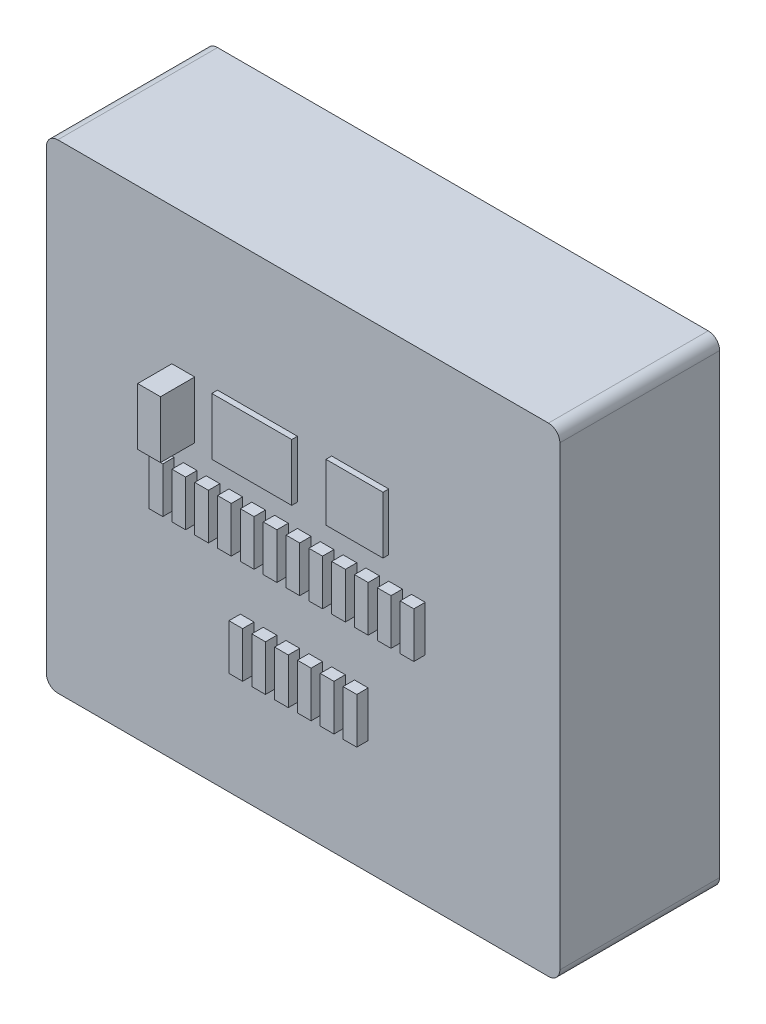
SolidWorks part; units mm, degrees
ref_plane "Front Plane" through (0, 0, 0) normal (0, 0, 1) x (1, 0, 0)
ref_plane "Top Plane" through (0, 0, 0) normal (0, 1, 0) x (1, 0, 0)
ref_plane "Right Plane" through (0, 0, 0) normal (1, 0, 0) x (0, 0, -1)
sketch "Sketch1" plane through (0, 0, 0) normal (0, 0, 1) x (1, 0, 0)
  line L1 (1, 0) -> (44, 0)
  line L2 (0, 1) -> (0, 41)
  line L3 (1, 42) -> (44, 42)
  line L4 (45, 1) -> (45, 41)
  arc A0 (1, 0) -> (0, 1) centre (1, 1) cw
  arc A1 (44, 0) -> (45, 1) centre (44, 1) ccw
  arc A2 (44, 42) -> (45, 41) centre (44, 41) cw
  arc A3 (0, 41) -> (1, 42) centre (1, 41) cw
  point P7 (0, 0)
  point P12 (45, 42)
  point P15 (0, 42)
  dimension "D3" = 1
  dimension "D1" = 42
  dimension "D2" = 45
extrude "Boss-Extrude1" add sketch "Sketch1" along normal blind 14
sketch "Sketch2" plane through (0, 0, 14) normal (0, 0, 1) x (1, 0, 0)
  line L0 (44, 42) -> (1, 42) construction
  line L1 (15, 30) -> (22, 30)
  line L2 (15, 30) -> (15, 25)
  line L3 (15, 25) -> (22, 25)
  line L4 (22, 30) -> (22, 25)
  line L5 (25, 30) -> (30, 30)
  line L6 (25, 30) -> (25, 25)
  line L7 (25, 25) -> (30, 25)
  line L8 (30, 30) -> (30, 25)
  line L9 (0, 41) -> (0, 1) construction
  line L10 (45, 1) -> (45, 41) construction
  dimension "D1" = 7
  dimension "D2" = 5
  dimension "D3" = 5
  dimension "D4" = 5
  dimension "D5" = 12
  dimension "D6" = 15
  dimension "D7" = 15
extrude "Boss-Extrude2" add sketch "Sketch2" along normal blind 0.5
sketch "Sketch3" plane through (0, 0, 14) normal (0, 0, 1) x (1, 0, 0)
  line L0 (0, 41) -> (0, 1) construction
  line L1 (10, 23) -> (11.2, 23)
  line L2 (10, 23) -> (10, 19)
  line L3 (10, 19) -> (11.2, 19)
  line L4 (11.2, 23) -> (11.2, 19)
  line L5 (1, 0) -> (44, 0) construction
  line L6 (12, 23) -> (13.2, 23)
  line L7 (13.2, 23) -> (13.2, 19)
  line L8 (12, 19) -> (13.2, 19)
  line L9 (12, 23) -> (12, 19)
  line L10 (14, 23) -> (15.2, 23)
  line L11 (15.2, 23) -> (15.2, 19)
  line L12 (14, 19) -> (15.2, 19)
  line L13 (14, 23) -> (14, 19)
  line L14 (16, 23) -> (17.2, 23)
  line L15 (17.2, 23) -> (17.2, 19)
  line L16 (16, 19) -> (17.2, 19)
  line L17 (16, 23) -> (16, 19)
  line L18 (18, 23) -> (19.2, 23)
  line L19 (19.2, 23) -> (19.2, 19)
  line L20 (18, 19) -> (19.2, 19)
  line L21 (18, 23) -> (18, 19)
  line L22 (20, 23) -> (21.2, 23)
  line L23 (21.2, 23) -> (21.2, 19)
  line L24 (20, 19) -> (21.2, 19)
  line L25 (20, 23) -> (20, 19)
  line L26 (22, 23) -> (23.2, 23)
  line L27 (23.2, 23) -> (23.2, 19)
  line L28 (22, 19) -> (23.2, 19)
  line L29 (22, 23) -> (22, 19)
  line L30 (24, 23) -> (25.2, 23)
  line L31 (25.2, 23) -> (25.2, 19)
  line L32 (24, 19) -> (25.2, 19)
  line L33 (24, 23) -> (24, 19)
  line L34 (26, 23) -> (27.2, 23)
  line L35 (27.2, 23) -> (27.2, 19)
  line L36 (26, 19) -> (27.2, 19)
  line L37 (26, 23) -> (26, 19)
  line L38 (28, 23) -> (29.2, 23)
  line L39 (29.2, 23) -> (29.2, 19)
  line L40 (28, 19) -> (29.2, 19)
  line L41 (28, 23) -> (28, 19)
  line L42 (30, 23) -> (31.2, 23)
  line L43 (31.2, 23) -> (31.2, 19)
  line L44 (30, 19) -> (31.2, 19)
  line L45 (30, 23) -> (30, 19)
  line L46 (32, 23) -> (33.2, 23)
  line L47 (33.2, 23) -> (33.2, 19)
  line L48 (32, 19) -> (33.2, 19)
  line L49 (32, 23) -> (32, 19)
  line L50 (19, 10) -> (20.2, 10)
  line L51 (17, 14) -> (18.2, 14)
  line L52 (17, 14) -> (17, 10)
  line L53 (17, 10) -> (18.2, 10)
  line L54 (18.2, 14) -> (18.2, 10)
  line L55 (19, 14) -> (19, 10)
  line L56 (20.2, 14) -> (20.2, 10)
  line L57 (19, 14) -> (20.2, 14)
  line L58 (21, 10) -> (22.2, 10)
  line L59 (21, 14) -> (21, 10)
  line L60 (22.2, 14) -> (22.2, 10)
  line L61 (21, 14) -> (22.2, 14)
  line L62 (23, 10) -> (24.2, 10)
  line L63 (23, 14) -> (23, 10)
  line L64 (24.2, 14) -> (24.2, 10)
  line L65 (23, 14) -> (24.2, 14)
  line L66 (25, 10) -> (26.2, 10)
  line L67 (25, 14) -> (25, 10)
  line L68 (26.2, 14) -> (26.2, 10)
  line L69 (25, 14) -> (26.2, 14)
  line L70 (27, 10) -> (28.2, 10)
  line L71 (27, 14) -> (27, 10)
  line L72 (28.2, 14) -> (28.2, 10)
  line L73 (27, 14) -> (28.2, 14)
  dimension "D1" = 4
  dimension "D2" = 1.2
  dimension "D3" = 10
  dimension "D4" = 19
  dimension "D6" = 0.8
  dimension "D7" = 10
  dimension "D8" = 17
  dimension "D10" = 0.8
  dimension "D5" = 12
  dimension "D9" = 6
extrude "Boss-Extrude3" add sketch "Sketch3" along normal blind 1
sketch "Sketch4" plane through (0, 0, 14) normal (0, 0, 1) x (1, 0, 0)
  line L0 (15, 30) -> (15, 25) construction
  line L1 (11, 30) -> (13, 30)
  line L2 (11, 30) -> (11, 25)
  line L3 (11, 25) -> (13, 25)
  line L4 (13, 30) -> (13, 25)
  line L5 (44, 42) -> (1, 42) construction
  dimension "D1" = 2
  dimension "D2" = 5
  dimension "D3" = 2
  dimension "D4" = 12
extrude "Boss-Extrude4" add sketch "Sketch4" along normal blind 3
